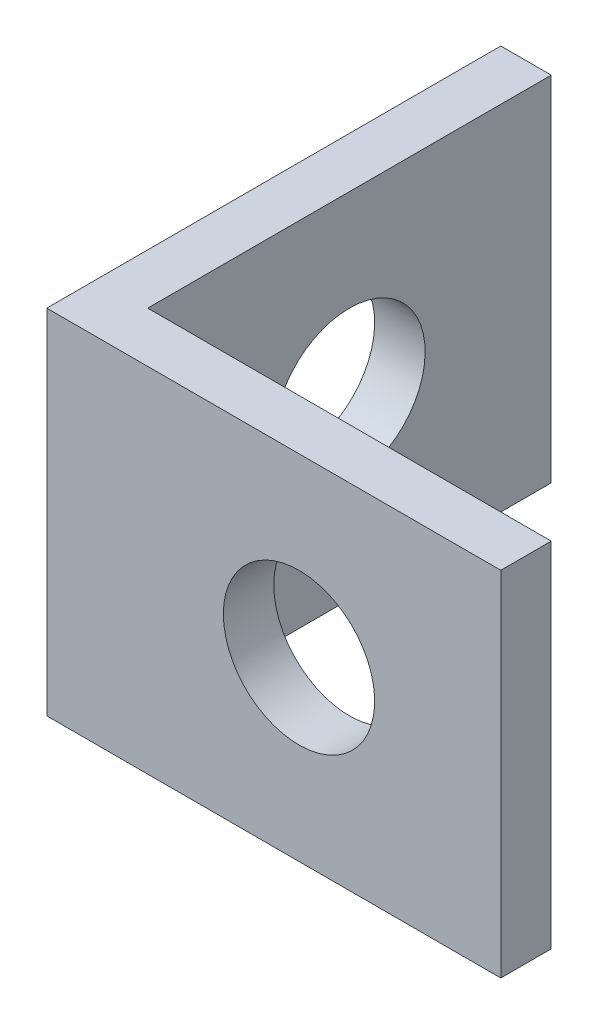
SolidWorks part; units mm, degrees
ref_plane "Plan de face" through (0, 0, 0) normal (0, 0, 1) x (1, 0, 0)
ref_plane "Plan de dessus" through (0, 0, 0) normal (0, 1, 0) x (1, 0, 0)
ref_plane "Plan de droite" through (0, 0, 0) normal (1, 0, 0) x (0, 0, -1)
sketch "Esquisse1" plane through (0, 0, 0) normal (0, 0, 1) x (1, 0, 0)
  line L0 (0, 10.3156) -> (0, -3.6144) construction
  line L1 (-4, 7) -> (4, 7)
  line L2 (-4, 7) -> (-4, 0)
  line L3 (-4, 0) -> (4, 0)
  line L4 (4, 7) -> (4, 0)
  dimension "D1" = 8
  dimension "D2" = 7
extrude "Boss.-Extru.1" add sketch "Esquisse1" along normal blind 1
sketch "Esquisse2" plane through (0, 0, 1) normal (0, 0, 1) x (1, 0, 0)
  line L1 (-4, 7) -> (-5, 7)
  line L2 (-4, 7) -> (-4, 0)
  line L3 (-4, 0) -> (-5, 0)
  line L4 (-5, 7) -> (-5, 0)
  dimension "D1" = 1
extrude "Boss.-Extru.2" add sketch "Esquisse2" against normal blind 9
sketch "Esquisse3" plane through (-4, 0, 0) normal (1, 0, 0) x (0, 0, -1)
  line L2 (8, 3.5) -> (0, 3.5) construction
  line L3 (8, 0) -> (8, 7) construction
  line L4 (0, 0) -> (0, 7) construction
  circle A0 centre (4, 3.5) radius 1.5
  dimension "D1" = 3
extrude "Enlèv. mat.-Extru.1" cut sketch "Esquisse3" against normal through all
sketch "Esquisse4" plane through (0, 0, 0) normal (0, 0, -1) x (-1, 0, 0)
  line L0 (0, 7) -> (0, 0) construction
  line L1 (-4, 7) -> (4, 7) construction
  line L2 (-4, 3.5) -> (0.6654, 3.5) construction
  line L3 (-4, 0) -> (-4, 7) construction
  circle A0 centre (0, 3.5) radius 1.5
  dimension "D2" = 3
extrude "Enlèv. mat.-Extru.2" cut sketch "Esquisse4" against normal through all
